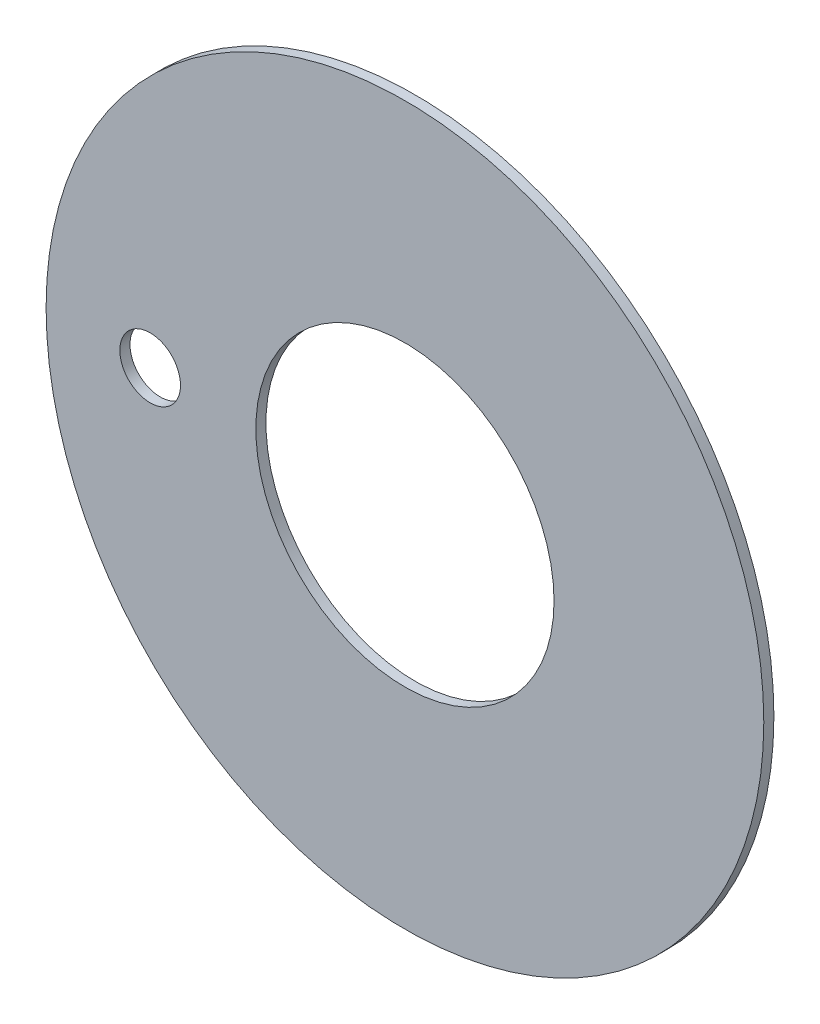
SolidWorks part; units mm, degrees
ref_plane "Plano frontal" through (0, 0, 0) normal (0, 0, 1) x (1, 0, 0)
ref_plane "Plano superior" through (0, 0, 0) normal (0, 1, 0) x (1, 0, 0)
ref_plane "Plano direito" through (0, 0, 0) normal (1, 0, 0) x (0, 0, -1)
sketch "Esboço2" plane through (0, 0, 0) normal (0, 0, 1) x (1, 0, 0)
  circle A0 centre (0, 0) radius 35.5
  point P3 (-6.8597, 2.5328)
  point P6 (-6.6627, -0.2852)
extrude "Ressalto-extrusão1" add sketch "Esboço2" along normal blind 1
sketch "Esboço3" plane through (0, 0, 1) normal (0, 0, 1) x (1, 0, 0)
  circle A0 centre (0, 0) radius 14.75
extrude "Corte-extrusão1" cut sketch "Esboço3" against normal blind 1
sketch "Esboço7" plane through (0, 0, 1) normal (0, 0, 1) x (1, 0, 0)
  circle A0 centre (-25.2036, 0) radius 3
extrude "Corte-extrusão3" cut sketch "Esboço7" against normal blind 1
